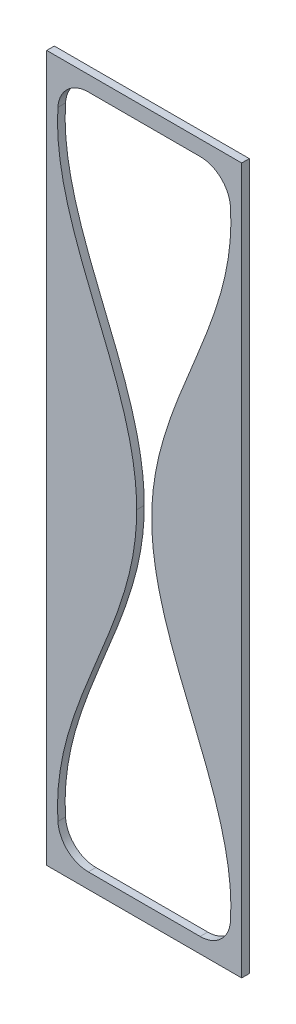
SolidWorks part; units mm, degrees
ref_plane "Front Plane" through (0, 0, 0) normal (0, 0, 1) x (1, 0, 0)
ref_plane "Top Plane" through (0, 0, 0) normal (0, 1, 0) x (1, 0, 0)
ref_plane "Right Plane" through (0, 0, 0) normal (1, 0, 0) x (0, 0, -1)
sketch "Sketch1" plane through (0, 0, 0) normal (0, 0, 1) x (1, 0, 0)
  line L0 (34.35, 6.35) -> (0, 6.35)
  line L1 (0, 0) -> (40.7, 0)
  line L2 (0, 0) -> (0, 147.32) construction
  line L3 (0, 147.32) -> (40.7, 147.32) construction
  line L4 (40.7, 0) -> (40.7, 147.32)
  line L5 (0, 0) -> (0, 6.35)
  line L6 (3.175, 147.32) -> (40.7, 147.32)
  spline S0 degree 3 poles (34.35, 6.35) (45.4155, 56.5451) (2.8524, 97.7877) (3.175, 147.32) knots 0 0 0 0 1 1 1 1
  point P7 (35.0089, 37.6597)
  point P9 (15.4206, 95.1743)
  dimension "D1" = 81.4
  dimension "D2" = 294.64
  dimension "D3" = 6.35
  dimension "D4" = 6.35
  dimension "D5" = 3.175
extrude "Boss-Extrude1" add sketch "Sketch1" along normal blind 3.175 contours S0 L6 L4 L1 L5 L0
mirror "Mirror1" about plane through (0, 0, 3.175) normal (-1, 0, 0) of bodies 101
mirror "Mirror2" about plane through (-3.175, 147.32, 3.175) normal (0, 1, 0) of bodies 102
fillet "Fillet1" radius 12.7 4 edges at (34.35, 6.35, 1.5875) (-34.35, 6.35, 1.5875) (34.35, 288.29, 1.5875) (-34.35, 288.29, 1.5875)
